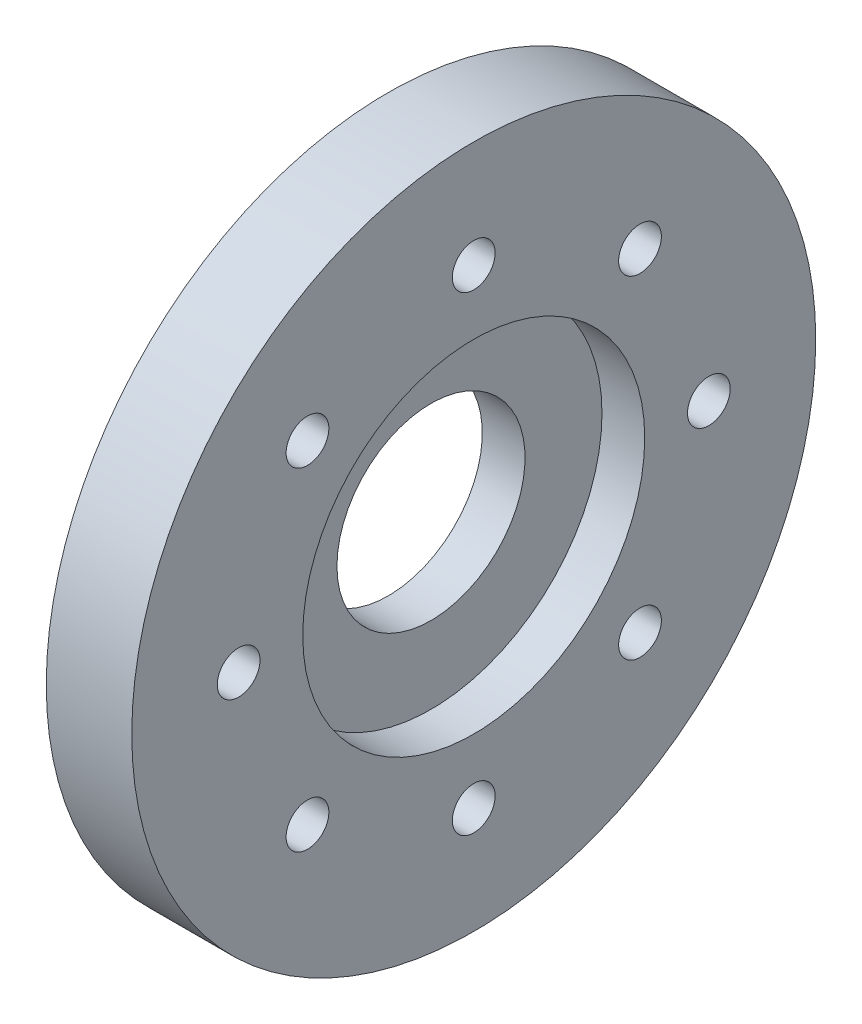
SolidWorks part; units mm, degrees
ref_plane "Front Plane" through (0, 0, 0) normal (0, 0, 1) x (1, 0, 0)
ref_plane "Top Plane" through (0, 0, 0) normal (0, 1, 0) x (1, 0, 0)
ref_plane "Right Plane" through (0, 0, 0) normal (1, 0, 0) x (0, 0, -1)
sketch "Sketch1" plane through (0, 0, 0) normal (0, 0, 1) x (1, 0, 0)
  line L0 (2.55, 40) -> (-7.45, 40)
  line L1 (-7.45, 40) -> (-7.45, 0)
  line L2 (-7.45, 0) -> (-2.45, 0)
  line L3 (-2.45, 20) -> (-2.45, -20) construction
  line L4 (-2.45, 0) -> (-2.45, 11)
  line L5 (-2.45, 11) -> (-7.45, 11)
  line L6 (-2.45, 11) -> (-2.45, 20)
  line L7 (-2.45, 20) -> (2.55, 20)
  line L8 (2.55, 20) -> (2.55, 40)
  dimension "D1" = 5
revolve "Revolve1" add sketch "Sketch1" angle 360 about L2
sketch "Sketch2" plane through (2.55, 0, 0) normal (1, 0, 0) x (0, 0, -1)
  circle A0 centre (-19.4454, -19.4454) radius 2.5
  circle A1 centre (-19.4454, -19.4454) radius 2.5 construction
  circle A2 centre (-27.5, 0) radius 2.5
  circle A3 centre (-19.4454, 19.4454) radius 2.5
  circle A4 centre (0, 27.5) radius 2.5
  circle A5 centre (19.4454, 19.4454) radius 2.5
  circle A6 centre (27.5, 0) radius 2.5
  circle A7 centre (19.4454, -19.4454) radius 2.5
  circle A8 centre (0, -27.5) radius 2.5
  point P6 (0, 0)
  point P21 (0, 0)
  dimension "D1" = 8
extrude "Cut-Extrude1" cut sketch "Sketch2" against normal through all
